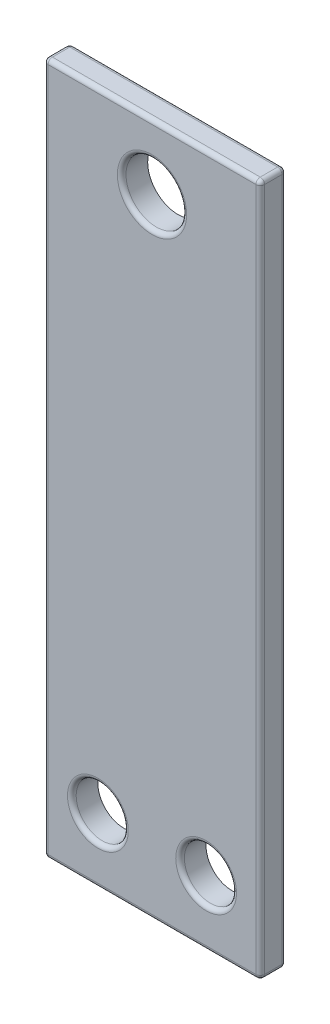
SolidWorks part; units mm, degrees
ref_plane "Alzado" through (0, 0, 0) normal (0, 0, 1) x (1, 0, 0)
ref_plane "Planta" through (0, 0, 0) normal (0, 1, 0) x (1, 0, 0)
ref_plane "Vista lateral" through (0, 0, 0) normal (1, 0, 0) x (0, 0, -1)
sketch "Croquis1" plane through (0, 0, 0) normal (0, 0, 1) x (1, 0, 0)
  line L0 (0, 0) -> (0, 32.5) construction
  line L1 (-12.5, -40) -> (12.5, -40)
  line L2 (-12.5, -40) -> (-12.5, 40)
  line L3 (-12.5, 40) -> (12.5, 40)
  line L4 (12.5, -40) -> (12.5, 40)
  line L5 (-12.5, -40) -> (12.5, 40) construction
  line L6 (-12.5, 40) -> (12.5, -40) construction
  line L7 (0, 0) -> (-12.5, 0) construction
  line L8 (0, -32.5) -> (12.5, -32.5) construction
  line L9 (0, -32.5) -> (0, -22.1927) construction
  circle A0 centre (0, 32.5) radius 3.5
  circle A2 centre (6.25, -32.5) radius 3.0093
  circle A3 centre (-6.25, -32.5) radius 3.0093
  point P0 (0, 0)
  dimension "D1" = 25
  dimension "D2" = 80
  dimension "D3" = 32.5
extrude "Saliente-Extruir1" add sketch "Croquis1" along normal blind 3
fillet "Redondeo1" radius 0.5 15 edges at (12.5, 0, 0) (12.5, -40, 1.5) (0, -40, 0) (12.5, 40, 1.5) (0, 40, 0) (-12.5, 40, 1.5) (-12.5, -40, 1.5) (-12.5, 0, 0) (3.5, 32.5, 3) (0, -40, 3) (-12.5, 0, 3) (0, 40, 3) (12.5, 0, 3) (-9.2593, -32.5, 3) (9.2593, -32.5, 3)
